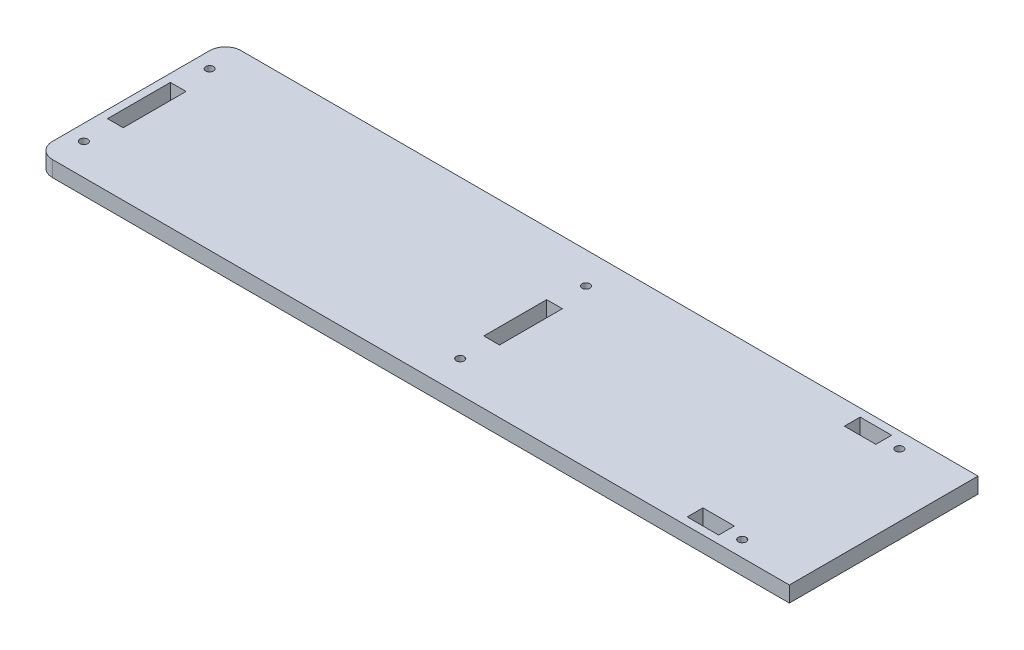
SolidWorks part; units mm, degrees
material "6061 Alloy"
ref_plane "Front Plane" through (0, 0, 0) normal (0, 0, 1) x (1, 0, 0)
ref_plane "Top Plane" through (0, 0, 0) normal (0, 1, 0) x (1, 0, 0)
ref_plane "Right Plane" through (0, 0, 0) normal (1, 0, 0) x (0, 0, -1)
sketch "Sketch1" plane through (0, 0, 0) normal (0, 1, 0) x (1, 0, 0)
  line L0 (-51.2351, -113.3334) -> (246.4593, -113.3334)
  line L1 (-51.2351, -37.1334) -> (246.4593, -37.1334)
  line L2 (246.4593, -37.1334) -> (246.4593, -113.3334)
  line L3 (-57.5851, -43.4834) -> (-57.5851, -106.9834)
  line L4 (-54.4101, -75.2334) -> (-54.4101, -62.5334)
  line L5 (-54.4101, -62.5334) -> (-48.0601, -62.5334)
  line L6 (-48.0601, -62.5334) -> (-48.0601, -87.9334)
  line L7 (-48.0601, -87.9334) -> (-54.4101, -87.9334)
  line L8 (-54.4101, -87.9334) -> (-54.4101, -75.2334)
  line L9 (97.6121, -75.2334) -> (97.6121, -62.5334)
  line L10 (97.6121, -62.5334) -> (103.9621, -62.5334)
  line L11 (103.9621, -62.5334) -> (103.9621, -87.9334)
  line L12 (103.9621, -87.9334) -> (97.6121, -87.9334)
  line L13 (97.6121, -87.9334) -> (97.6121, -75.2334)
  line L14 (208.3593, -103.8084) -> (202.0093, -103.8084)
  line L15 (202.0093, -103.8084) -> (202.0093, -110.1584)
  line L16 (202.0093, -110.1584) -> (214.7093, -110.1584)
  line L17 (214.7093, -110.1584) -> (214.7093, -103.8084)
  line L18 (214.7093, -103.8084) -> (208.3593, -103.8084)
  line L19 (208.3593, -46.6584) -> (202.0093, -46.6584)
  line L20 (202.0093, -46.6584) -> (202.0093, -40.3084)
  line L21 (202.0093, -40.3084) -> (214.7093, -40.3084)
  line L22 (214.7093, -40.3084) -> (214.7093, -46.6584)
  line L23 (214.7093, -46.6584) -> (208.3593, -46.6584)
  circle A0 centre (-51.2351, -100.6334) radius 1.5875
  circle A1 centre (-51.2351, -49.8334) radius 1.5875
  circle A2 centre (100.7871, -100.6334) radius 1.5875
  circle A3 centre (100.7871, -49.8334) radius 1.5875
  circle A4 centre (221.0593, -106.9834) radius 1.5875
  circle A5 centre (221.0593, -43.4834) radius 1.5875
  arc A6 (-57.5851, -106.9834) -> (-51.2351, -113.3334) centre (-51.2351, -106.9834) ccw
  arc A7 (-51.2351, -37.1334) -> (-57.5851, -43.4834) centre (-51.2351, -43.4834) ccw
extrude "Boss-Extrude1" add sketch "Sketch1" along normal blind 6.35
